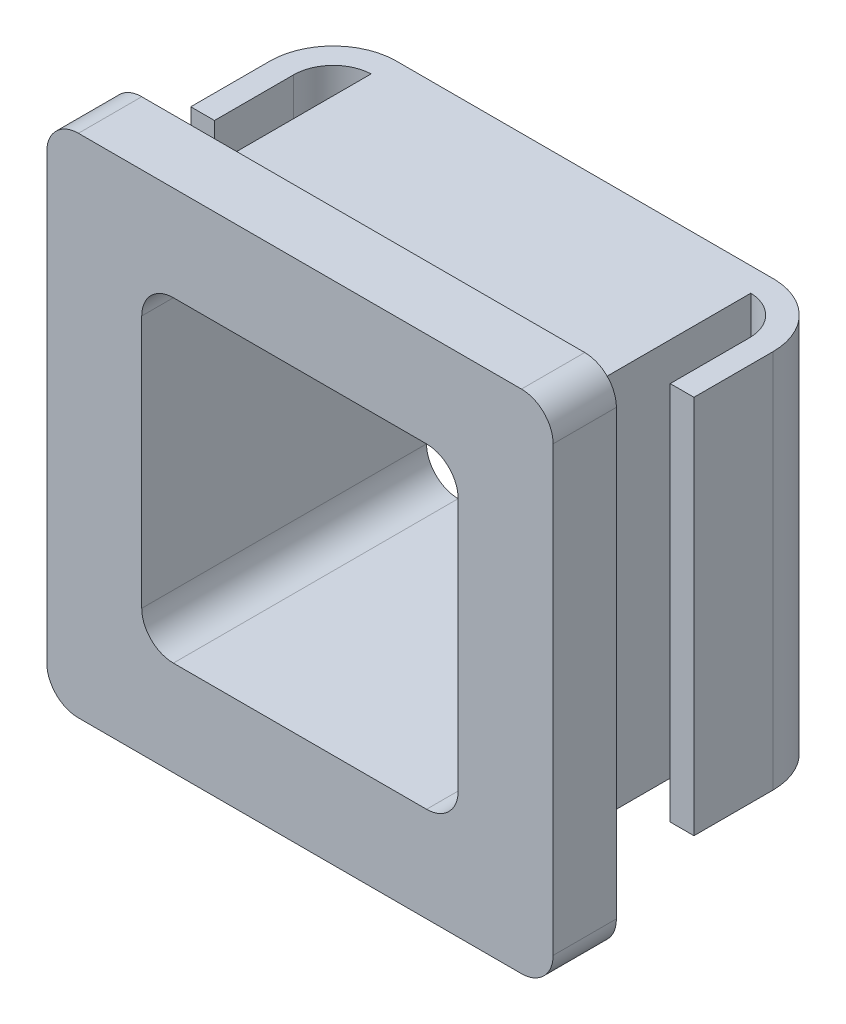
SolidWorks part; units mm, degrees
ref_plane "Front Plane" through (0, 0, 0) normal (0, 0, 1) x (1, 0, 0)
ref_plane "Top Plane" through (0, 0, 0) normal (0, 1, 0) x (1, 0, 0)
ref_plane "Right Plane" through (0, 0, 0) normal (1, 0, 0) x (0, 0, -1)
sketch "Sketch1" plane through (0, 0, 0) normal (0, 0, 1) x (1, 0, 0)
  line L1 (-8, -8) -> (8, -8)
  line L2 (-8, -8) -> (-8, 8)
  line L3 (-8, 8) -> (8, 8)
  line L4 (8, -8) -> (8, 8)
  line L5 (-8, -8) -> (8, 8) construction
  line L6 (-8, 8) -> (8, -8) construction
  line L7 (-5, -5) -> (5, -5)
  line L8 (-5, -5) -> (-5, 5)
  line L9 (-5, 5) -> (5, 5)
  line L10 (5, -5) -> (5, 5)
  line L11 (-5, -5) -> (5, 5) construction
  line L12 (-5, 5) -> (5, -5) construction
  point P0 (0, 0)
  point P6 (0, 0)
  dimension "D1" = 16
  dimension "D2" = 16
  dimension "D3" = 10
extrude "Boss-Extrude1" add sketch "Sketch1" along normal blind 2
sketch "Sketch2" plane through (0, 0, 0) normal (0, 0, 1) x (1, 0, 0)
  line L1 (6, -6) -> (-6, -6)
  line L2 (6, -6) -> (6, 6)
  line L3 (6, 6) -> (-6, 6)
  line L4 (-5, -5) -> (5, -5)
  line L5 (5, -5) -> (5, 5)
  line L6 (5, 5) -> (-5, 5)
  line L7 (-5, 5) -> (-5, -5)
  line L8 (-5, -5) -> (5, -5)
  line L9 (5, -5) -> (5, 5)
  line L10 (5, 5) -> (-5, 5)
  line L11 (-5, 5) -> (-5, -5)
  line L12 (-8, -8) -> (8, -8)
  line L13 (8, -8) -> (8, 8)
  line L14 (8, 8) -> (-8, 8)
  line L15 (-8, 8) -> (-8, -8)
  line L16 (-8, -8) -> (8, -8)
  line L17 (8, -8) -> (8, 8)
  line L18 (8, 8) -> (-8, 8)
  line L19 (-8, 8) -> (-8, -8)
  line L20 (-6, -6) -> (-6, 6)
  line L21 (6, -6) -> (-6, 6) construction
  line L22 (6, 6) -> (-6, -6) construction
  point P6 (0, 0)
  dimension "D3" = 12
  dimension "D4" = 12
  dimension "D1" = 0
  dimension "D2" = 0
extrude "Boss-Extrude2" add sketch "Sketch2" against normal blind 7 contours L20 L1 L2 L3 L11 L10 L9 L8
sketch "Sketch3" plane through (0, 6, 0) normal (0, 1, 0) x (1, 0, 0)
  line L0 (-6, 7) -> (-6, 6.2496)
  line L1 (-6, 7) -> (-6, 0) construction
  line L2 (-7.9506, 5) -> (-7.9506, 2.5)
  line L3 (-7.9506, 2.5) -> (-7.2006, 2.5)
  line L4 (-7.2006, 2.5) -> (-7.2006, 5)
  arc A0 (-6, 7) -> (-7.9506, 5) centre (-5.95, 5) ccw
  arc A1 (-6, 6.2496) -> (-7.2006, 5) centre (-5.95, 5) ccw
  arc A3 (-6, 7) -> (-6.8447, 3.2106) centre (-5.95, 5) ccw construction
  arc A4 (-5.9813, 6.2502) -> (-6.5093, 3.8814) centre (-5.95, 5) ccw construction
  dimension "D4" = 2
  dimension "D1" = 2.5
  dimension "D2" = 0.05
  dimension "D3" = 0.75
extrude "Boss-Extrude3" add sketch "Sketch3" against normal up to surface (12 mm away) up to face at (0, -6, -3.5)
mirror "Mirror1" about plane through (0, 0, 0) normal (1, 0, 0) of "Boss-Extrude3"
fillet "Fillet1" radius 1 10 edges at (6, 0, -7) (-6, 0, -7) (5, -5, -2.5) (-5, -5, -2.5) (-5, 5, -2.5) (5, 5, -2.5) (-8, 8, 1) (-8, -8, 1) (8, -8, 1) (8, 8, 1)
